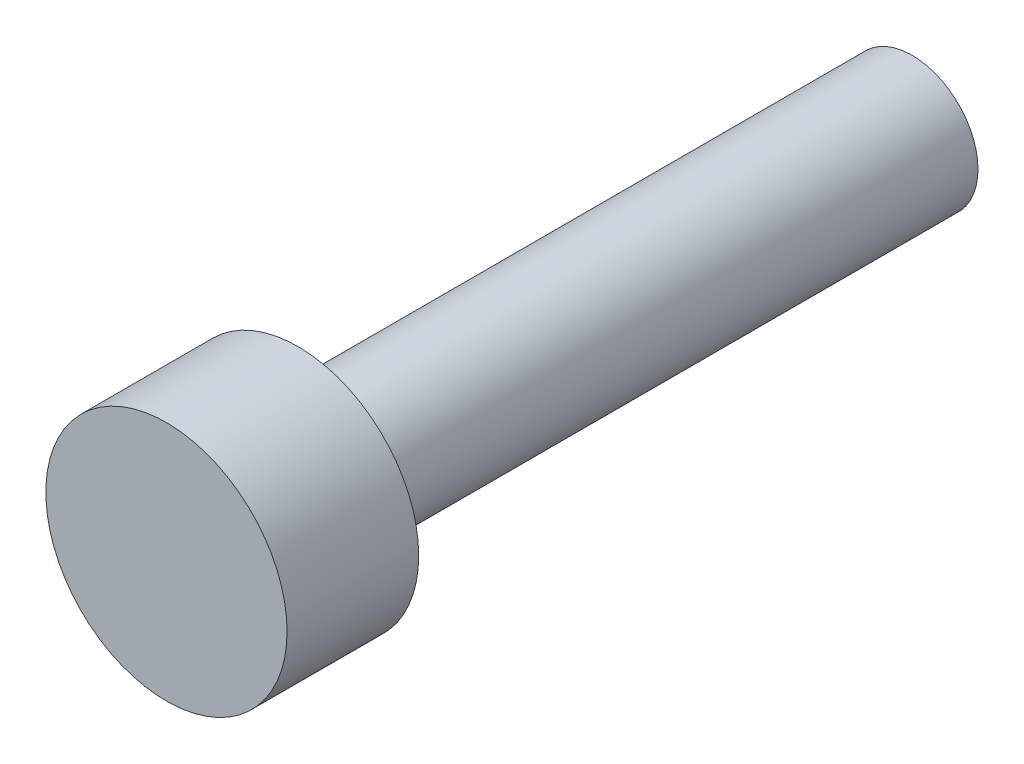
SolidWorks part; units mm, degrees
ref_plane "前视基准面" through (0, 0, 0) normal (0, 0, 1) x (1, 0, 0)
ref_plane "上视基准面" through (0, 0, 0) normal (0, 1, 0) x (1, 0, 0)
ref_plane "右视基准面" through (0, 0, 0) normal (1, 0, 0) x (0, 0, -1)
other "Configuration Table"
sketch "草图1" plane through (0, 0, 0) normal (0, 0, 1) x (1, 0, 0)
  circle A0 centre (0, 0) radius 1.5
extrude "M3杆" add sketch "草图1" along normal blind 14
sketch "草图2" plane through (0, 0, 0) normal (0, 0, 1) x (1, 0, 0)
  circle A0 centre (0, 0) radius 2.75
extrude "螺钉头" add sketch "草图2" along normal blind 3 from offset 14
